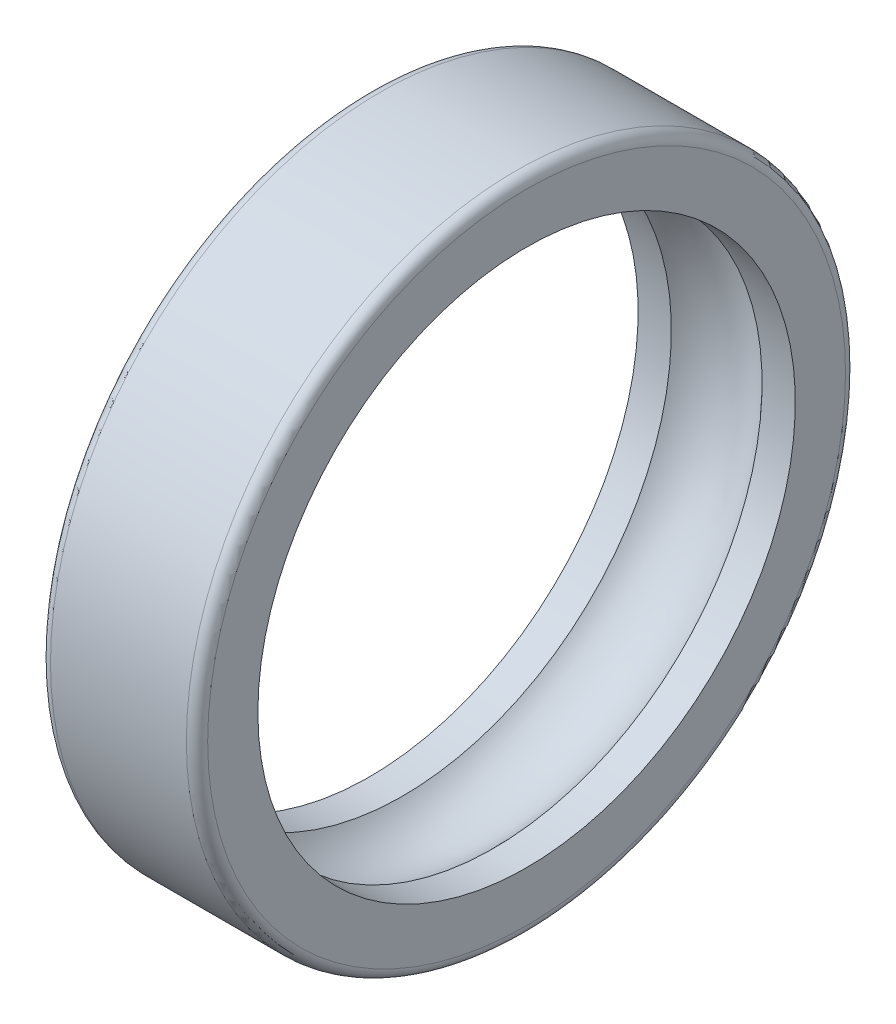
SolidWorks part; units mm, degrees
ref_plane "Front Plane" through (0, 0, 0) normal (0, 0, 1) x (1, 0, 0)
ref_plane "Top Plane" through (0, 0, 0) normal (0, 1, 0) x (1, 0, 0)
ref_plane "Right Plane" through (0, 0, 0) normal (1, 0, 0) x (0, 0, -1)
sketch "Sketch1" plane through (0, 0, 0) normal (0, 0, 1) x (1, 0, 0)
  line L0 (-25.3585, 0) -> (48.5277, 0) construction
  line L1 (0, 0) -> (0, 53) construction
  line L2 (-15.5, 65) -> (15.5, 65)
  line L3 (-15.5, 65) -> (-15.5, 53)
  line L4 (-15.5, 53) -> (-8.9443, 53)
  line L5 (15.5, 65) -> (15.5, 53)
  line L6 (-15.5, 65) -> (15.5, 53) construction
  line L7 (-15.5, 53) -> (15.5, 65) construction
  line L8 (8.9443, 53) -> (15.5, 53)
  arc A0 (-8.9443, 53) -> (8.9443, 53) centre (0, 45) cw
  point P3 (0, 59)
  dimension "D4" = 12
  dimension "D1" = 31
  dimension "D2" = 53
  dimension "D3" = 65
  dimension "D5" = 8
revolve "Revolve1" add sketch "Sketch1" angle 360 about L0
fillet "Fillet1" radius 2.1 2 edges at (15.5, 0, 65) (-15.5, 0, 65)
scale "Scale1" scale about centroid uniform scaling yes scale factor 0.19304
